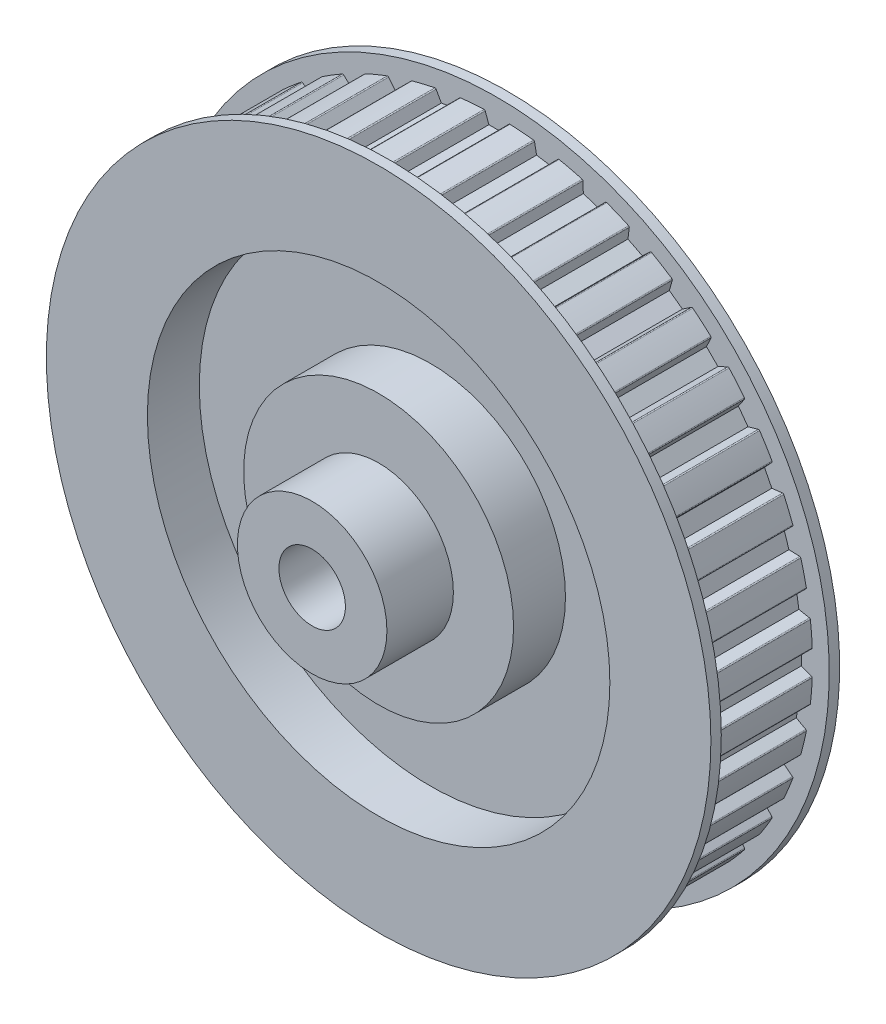
SolidWorks part; units mm, degrees
ref_plane "Front Plane" through (0, 0, 0) normal (0, 0, 1) x (1, 0, 0)
ref_plane "Top Plane" through (0, 0, 0) normal (0, 1, 0) x (1, 0, 0)
ref_plane "Right Plane" through (0, 0, 0) normal (1, 0, 0) x (0, 0, -1)
sketch "Sketch1" plane through (0, 0, 0) normal (0, 1, 0) x (1, 0, 0)
  line L0 (63.5, -10.3187) -> (0, -10.3187)
  line L1 (0, -10.3187) -> (0, -12.3031)
  line L2 (0, -12.3031) -> (63.5, -12.3031)
  line L3 (63.5, -12.3031) -> (63.5, -10.3187)
  line L4 (0, -10.3187) -> (0, -12.3031) construction
  dimension "D1" = 63.5
  dimension "D2" = 1.9844
revolve "Revolve1" add sketch "Sketch1" angle 360 about L4
sketch "Sketch2" plane through (0, 0, 10.3187) normal (0, 0, -1) x (-1, 0, 0)
  line L0 (20.8148, -56.5864) -> (19.4459, -54.8343)
  line L1 (19.4459, -54.8343) -> (16.4988, -55.7919)
  line L2 (16.4988, -55.7919) -> (16.4212, -58.014)
  line L3 (-25.2944, -54.7309) -> (-25.0234, -52.524)
  line L4 (-25.0234, -52.524) -> (-27.7845, -51.1172)
  line L5 (-27.7845, -51.1172) -> (-29.4106, -52.6336)
  line L6 (-52.6336, -29.4106) -> (-51.1172, -27.7845)
  line L7 (-51.1172, -27.7845) -> (-52.524, -25.0234)
  line L8 (-52.524, -25.0234) -> (-54.7309, -25.2944)
  line L9 (-58.014, 16.4212) -> (-55.7919, 16.4988)
  line L10 (-55.7919, 16.4988) -> (-54.8343, 19.4459)
  line L11 (-54.8343, 19.4459) -> (-56.5864, 20.8148)
  line L12 (-37.2822, 47.3848) -> (-35.4389, 46.1414)
  line L13 (-35.4389, 46.1414) -> (-32.9319, 47.9629)
  line L14 (-32.9319, 47.9629) -> (-33.5448, 50.1002)
  line L15 (7.1436, 59.8686) -> (7.5678, 57.686)
  line L16 (7.5678, 57.686) -> (10.6285, 57.2012)
  line L17 (10.6285, 57.2012) -> (11.7064, 59.1459)
  line L18 (40.9692, 44.2358) -> (40.0295, 42.2207)
  line L19 (40.0295, 42.2207) -> (42.2207, 40.0295)
  line L20 (42.2207, 40.0295) -> (44.2358, 40.9692)
  line L21 (59.1459, 11.7064) -> (57.2012, 10.6285)
  line L22 (57.2012, 10.6285) -> (57.686, 7.5678)
  line L23 (57.686, 7.5678) -> (59.8686, 7.1436)
  line L24 (50.1002, -33.5448) -> (47.9629, -32.9319)
  line L25 (47.9629, -32.9319) -> (46.1414, -35.4389)
  line L26 (46.1414, -35.4389) -> (47.3848, -37.2822)
  arc A0 (47.3848, -37.2822) -> (20.8148, -56.5864) centre (0, 0) cw
  arc A1 (16.4212, -58.014) -> (-25.2944, -54.7309) centre (0, 0) cw
  arc A2 (-29.4106, -52.6336) -> (-52.6336, -29.4106) centre (0, 0) cw
  arc A3 (-54.7309, -25.2944) -> (-58.014, 16.4212) centre (0, 0) cw
  arc A4 (-56.5864, 20.8148) -> (-37.2822, 47.3848) centre (0, 0) cw
  arc A5 (-33.5448, 50.1002) -> (7.1436, 59.8686) centre (0, 0) cw
  arc A6 (11.7064, 59.1459) -> (40.9692, 44.2358) centre (0, 0) cw
  arc A7 (44.2358, 40.9692) -> (59.1459, 11.7064) centre (0, 0) cw
  arc A8 (59.8686, 7.1436) -> (50.1002, -33.5448) centre (0, 0) cw
  circle A9 centre (0, 0) radius 63.5 construction
  dimension "D1" = 60.2933
  dimension "D2" = 60.2933
  dimension "D3" = 60.2933
  dimension "D4" = 60.2932
  dimension "D5" = 60.2933
  dimension "D6" = 60.2933
  dimension "D7" = 60.2932
  dimension "D8" = 60.2933
  dimension "D9" = 60.2933
  dimension "D10" = 7.1436
  dimension "D11" = 7.5678
  dimension "D12" = 10.6285
  dimension "D13" = 11.7064
  dimension "D14" = 16.4212
  dimension "D15" = 16.4988
  dimension "D16" = 19.4459
  dimension "D17" = 20.8148
  dimension "D18" = 40.0295
  dimension "D19" = 40.9692
  dimension "D20" = 42.2207
  dimension "D21" = 44.2358
  dimension "D22" = 46.1414
  dimension "D23" = 47.3848
  dimension "D24" = 47.9629
  dimension "D25" = 50.1002
  dimension "D26" = 57.2012
  dimension "D27" = 57.686
  dimension "D28" = 59.1459
  dimension "D29" = 59.8686
  dimension "D30" = 25.0234
  dimension "D31" = 25.2944
  dimension "D32" = 27.7845
  dimension "D33" = 29.4106
  dimension "D34" = 32.9319
  dimension "D35" = 33.5448
  dimension "D36" = 35.4389
  dimension "D37" = 37.2822
  dimension "D38" = 51.1172
  dimension "D39" = 52.524
  dimension "D40" = 52.6336
  dimension "D41" = 54.7309
  dimension "D42" = 54.8343
  dimension "D43" = 55.7919
  dimension "D44" = 56.5864
  dimension "D45" = 58.014
  dimension "D46" = 7.1436
  dimension "D47" = 7.5678
  dimension "D48" = 10.6285
  dimension "D49" = 11.7064
  dimension "D51" = 16.4988
  dimension "D52" = 19.4459
  dimension "D54" = 40.0295
  dimension "D56" = 42.2207
  dimension "D58" = 46.1414
  dimension "D60" = 47.9629
  dimension "D62" = 57.2012
  dimension "D63" = 57.686
  dimension "D66" = 25.0234
  dimension "D68" = 27.7845
  dimension "D70" = 32.9319
  dimension "D72" = 35.4389
  dimension "D74" = 51.1172
  dimension "D75" = 52.524
  dimension "D78" = 54.8343
  dimension "D79" = 55.7919
extrude "Boss-Extrude1" add sketch "Sketch2" along normal blind 20.6375
ref_plane "Plane1" through (0, 0, -10.3187) normal (0, 0, 1) x (1, 0, 0)
sketch "Sketch3" plane through (0, 0, -10.3187) normal (0, 0, 1) x (1, 0, 0)
  circle A0 centre (0, 0) radius 63.5
  dimension "D1" = 127
extrude "Boss-Extrude2" add sketch "Sketch3" against normal blind 1.9844
hole_wizard "Hole1" positions "Sketch5" profile "Sketch4" legacy
sketch "Sketch5" plane through (0, 0, -12.3031) normal (0, 0, -1) x (-1, 0, 0)
  point P0 (0, 0)
sketch "Sketch4" plane through (0, 0, -12.3031) normal (1, 0, 0) x (0, 1, 0)
  line L0 (0, 0) -> (0, 9.9219)
  line L1 (0, 9.9219) -> (44.1912, 9.9219)
  line L2 (44.1912, 9.9219) -> (44.1912, 0)
  line L3 (44.1912, 0) -> (0, 0)
  line L4 (0, 110) -> (0, -10) construction
  dimension "Diameter" = 88.3825
  dimension "Depth" = 9.9219
hole_wizard "Hole2" positions "Sketch7" profile "Sketch6" legacy
sketch "Sketch7" plane through (0, 0, 12.3031) normal (0, 0, 1) x (1, 0, 0)
  point P0 (0, 0)
sketch "Sketch6" plane through (0, 0, 12.3031) normal (1, 0, 0) x (0, -1, 0)
  line L0 (0, 0) -> (0, 9.9219)
  line L1 (0, 9.9219) -> (44.1912, 9.9219)
  line L2 (44.1912, 9.9219) -> (44.1912, 0)
  line L3 (44.1912, 0) -> (0, 0)
  line L4 (0, 110) -> (0, -10) construction
  dimension "Diameter" = 88.3825
  dimension "Depth" = 9.9219
sketch "Sketch8" plane through (0, 0, 0) normal (0, 1, 0) x (1, 0, 0)
  line L0 (14.2875, 12.3031) -> (0, 12.3031)
  line L1 (0, 12.3031) -> (0, 2.3813)
  line L2 (0, 2.3813) -> (14.2875, 2.3813)
  line L3 (14.2875, 2.3813) -> (14.2875, 12.3031)
  line L4 (0, 12.3031) -> (0, 2.3813) construction
  dimension "D1" = 14.2875
  dimension "D2" = 9.9219
revolve "Revolve2" add sketch "Sketch8" angle 360 about L4
sketch "Sketch9" plane through (0, 0, 0) normal (0, 1, 0) x (1, 0, 0)
  line L0 (25.7889, -2.3812) -> (0, -2.3813)
  line L1 (0, -2.3813) -> (0, -25.0031)
  line L2 (0, -25.0031) -> (14.2875, -25.0031)
  line L3 (14.2875, -25.0031) -> (14.2875, -12.3031)
  line L4 (14.2875, -12.3031) -> (25.7889, -12.3031)
  line L5 (25.7889, -12.3031) -> (25.7889, -2.3812)
  line L6 (0, -2.3813) -> (0, -25.0031) construction
  dimension "D1" = 14.2875
  dimension "D2" = 25.7889
  dimension "D3" = 12.7
  dimension "D4" = 22.6219
revolve "Revolve3" add sketch "Sketch9" angle 360 about L6
hole_wizard "Hole3" positions "Sketch11" profile "Sketch10" legacy
sketch "Sketch11" plane through (0, 0, 25.0031) normal (0, 0, 1) x (1, 0, 0)
  point P0 (0, 0)
sketch "Sketch10" plane through (0, 0, 25.0031) normal (1, 0, 0) x (0, -1, 0)
  line L0 (0, 0) -> (0, 37.3062)
  line L1 (0, 37.3062) -> (6.3564, 37.3062)
  line L2 (6.3564, 37.3062) -> (6.3564, 0)
  line L3 (6.3564, 0) -> (0, 0)
  line L4 (0, 110) -> (0, -10) construction
  dimension "Diameter" = 12.7127
  dimension "Depth" = 37.3062
fillet "Fillet1" radius 0.2286 18 edges at (-7.1436, 59.8686, 0) (58.014, 16.4212, 0) (52.6336, -29.4106, 0) (-59.1459, 11.7064, 0) (37.2822, 47.3848, 0) (-59.8686, 7.1436, 0) (-44.2358, 40.9692, 0) (-50.1002, -33.5448, 0) (54.7309, -25.2944, 0) (-47.3848, -37.2822, 0) (56.5864, 20.8148, 0) (-20.8148, -56.5864, 0) (33.5448, 50.1002, 0) (-16.4212, -58.014, 0) (-11.7064, 59.1459, 0) (25.2944, -54.7309, 0) (-40.9692, 44.2358, 0) (29.4106, -52.6336, 0)
sketch "Sketch12" plane through (0, 0, -10.3187) normal (0, 0, 1) x (1, 0, 0)
  line L0 (35.4389, 46.1414) -> (37.1438, 47.2914) construction
  line L1 (32.9319, 47.9629) -> (35.4389, 46.1414) construction
  line L2 (33.4987, 49.9397) -> (32.9319, 47.9629) construction
  line L3 (35.4389, 46.1414) -> (37.1438, 47.2914)
  line L4 (32.9319, 47.9629) -> (35.4389, 46.1414)
  line L5 (33.4987, 49.9397) -> (32.9319, 47.9629)
  arc A0 (37.4135, 47.2812) -> (37.1438, 47.2914) centre (37.2716, 47.1019) ccw construction
  arc A1 (33.4987, 49.9397) -> (33.4057, 50.193) centre (33.279, 50.0027) ccw construction
  arc A2 (37.4135, 47.2812) -> (37.1438, 47.2914) centre (37.2716, 47.1019) ccw
  arc A3 (33.4987, 49.9397) -> (33.4057, 50.193) centre (33.279, 50.0027) ccw
  arc A4 (33.4057, 50.193) -> (37.4135, 47.2812) centre (0.056, 0.0771) cw
  dimension "D1" = 60.198
extrude "Cut-Extrude1" cut sketch "Sketch12" along normal blind 20.6502
pattern_circular "CirPattern2" count 40 over 360 about axis through (0, 0, 0) along (0, 0, 1) of "Cut-Extrude1"
equation "\"0.8125in.\"=0.813"
equation "\"D1@Cut-Extrude1\"=\"0.8125in.\""
